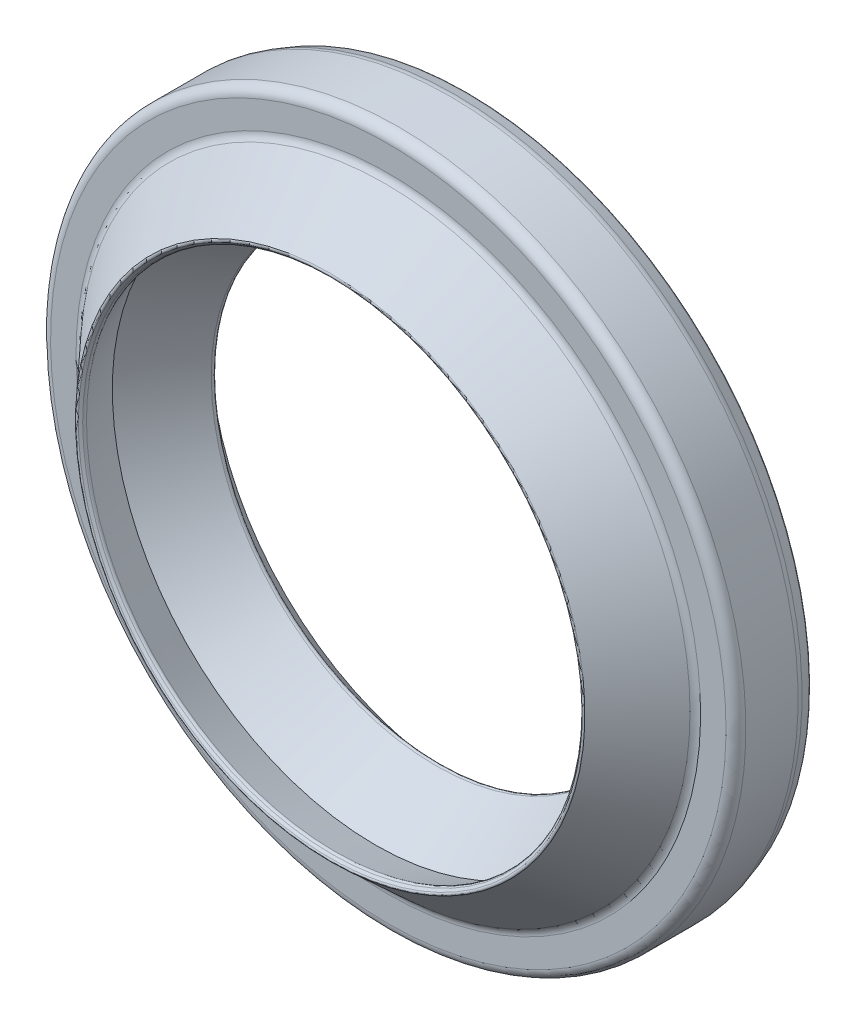
SolidWorks part; units mm, degrees
material "EPDM 60 дюрометр"
ref_plane "Спереди" through (0, 0, 0) normal (0, 0, 1) x (1, 0, 0)
ref_plane "Сверху" through (0, 0, 0) normal (0, 1, 0) x (1, 0, 0)
ref_plane "Справа" through (0, 0, 0) normal (1, 0, 0) x (0, 0, -1)
sketch "Эскиз1" plane through (0, 0, 0) normal (1, 0, 0) x (0, 0, -1)
  line L0 (0, 0) -> (-8, 0) construction
  line L1 (-14, 0) -> (-14, 35) construction
  line L2 (0, 0) -> (0, 25) construction
  line L3 (-13.6341, 25.1341) -> (-14, 25.5)
  line L4 (-14, 25.5) -> (-8, 31)
  line L5 (-8, 31) -> (-8, 35)
  line L6 (-8, 35) -> (-1.5, 35)
  line L7 (-1.5, 35) -> (0, 34.5)
  line L8 (0, 34.5) -> (0, 31.5)
  line L9 (0, 31.5) -> (-7, 31.5)
  line L10 (-7, 31.5) -> (-7, 27.5)
  line L11 (-7, 27.5) -> (-1.75, 27.5)
  line L12 (0, 31.5) -> (0, 26.5) construction
  line L13 (-13.3214, 25.0636) -> (-9.2839, 26.5)
  line L14 (-9.2839, 26.5) -> (-3.1996, 22.624)
  line L15 (-0.25, 27.5) -> (-0.25, 25.7035)
  line L16 (-0.25, 25.7035) -> (-2.8095, 22.6831)
  line L17 (0, 25) -> (-16.6622, 25) construction
  arc A0 (-1.75, 27.5) -> (-0.25, 27.5) centre (-1, 27.5) ccw
  arc A1 (-3.1996, 22.624) -> (-2.8095, 22.6831) centre (-3.0384, 22.877) ccw
  arc A2 (-13.6341, 25.1341) -> (-13.3214, 25.0636) centre (-13.4219, 25.3462) ccw
  point P3 (-14, 0)
  point P4 (-13.5, 25)
  point P8 (0, 34.5)
  point P10 (-14, 25.5)
  point P11 (-1.5, 35)
  point P12 (-8, 31)
  point P33 (-13.5, 25)
  dimension "D15" = 1.5
  dimension "D17" = 0.3
  dimension "D1" = 8
  dimension "D2" = 14
  dimension "D3" = 25
  dimension "D4" = 35
  dimension "D5" = 1
  dimension "D6" = 0.5
  dimension "D7" = 10
  dimension "D8" = 0.5
  dimension "D9" = 1.5
  dimension "D10" = 6
  dimension "D11" = 3
  dimension "D12" = 7
  dimension "D13" = 4
  dimension "D14" = 6
  dimension "D16" = 5
sketch "Эскиз2" plane through (0, 0, 0) normal (1, 0, 0) x (0, 0, -1)
  line L0 (97.746, 203.2468) -> (1097.746, 203.2468) construction
revolve "Повернуть1" add sketch "Эскиз1" angle 360 about L0
fillet "Скругление1" radius 1 1 edges at (0, 31, 8)
fillet "Скругление2" radius 0.2 1 edges at (0, 25.5, 14)
fillet "Скругление3" radius 1 1 edges at (0, 35, 8)
fillet "Скругление4" radius 0.3 1 edges at (0, 34.5, 0)
fillet "Скругление5" radius 1.5 1 edges at (0, 35, 1.5)
fillet "Скругление6" radius 0.3 1 edges at (0, 31.5, 0)
fillet "Скругление7" radius 0.5 1 edges at (0, 31.5, 7)
fillet "Скругление8" radius 0.3 1 edges at (0, 27.5, 7)
sketch "Эскиз5" plane through (0, 0, 0) normal (1, 0, 0) x (0, 0, -1)
  line L0 (0, 0) -> (9.7597, 0) construction
  circle A0 centre (-1, 27.5) radius 0.75
revolve "Повернуть2" add sketch "Эскиз5" angle 360 about L0
